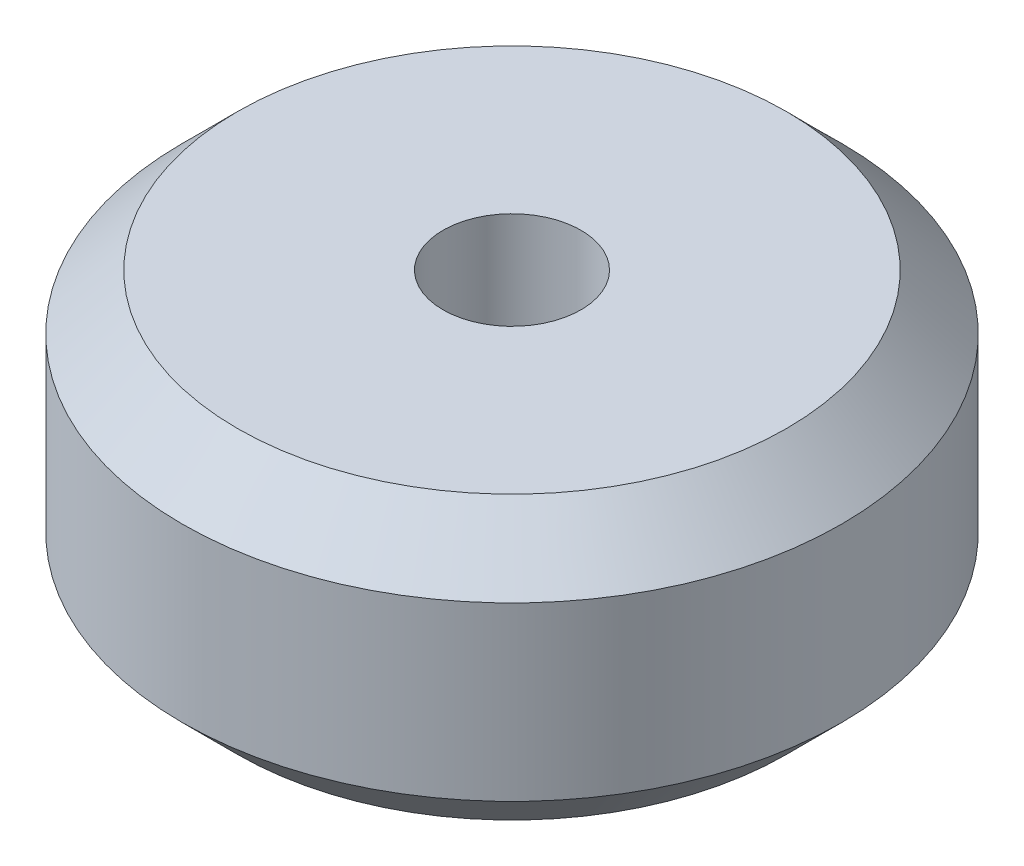
SolidWorks part; units mm, degrees
ref_plane "Front Plane" through (0, 0, 0) normal (0, 0, 1) x (1, 0, 0)
ref_plane "Top Plane" through (0, 0, 0) normal (0, 1, 0) x (1, 0, 0)
ref_plane "Right Plane" through (0, 0, 0) normal (1, 0, 0) x (0, 0, -1)
sketch "Sketch1" plane through (0, 0, 0) normal (0, 1, 0) x (1, 0, 0)
  circle A0 centre (0, 0) radius 7.985
  circle A1 centre (0, 0) radius 11.95
  dimension "D1" = 23.9
  dimension "D2" = 15.97
extrude "Boss-Extrude1" add sketch "Sketch1" along normal blind 10.23
chamfer "Chamfer1" distance 2 angle 45 2 edges at (0, 0, 11.95) (0, 10.23, 11.95)
sketch "Sketch2" plane through (0, 0, 0) normal (0, 1, 0) x (1, 0, 0)
  circle A0 centre (0, 0) radius 7.985
  circle A1 centre (0, 0) radius 2.5
  dimension "D1" = 5
  dimension "D2" = 15.97
extrude "Boss-Extrude3" add sketch "Sketch2" along normal blind 10.23
